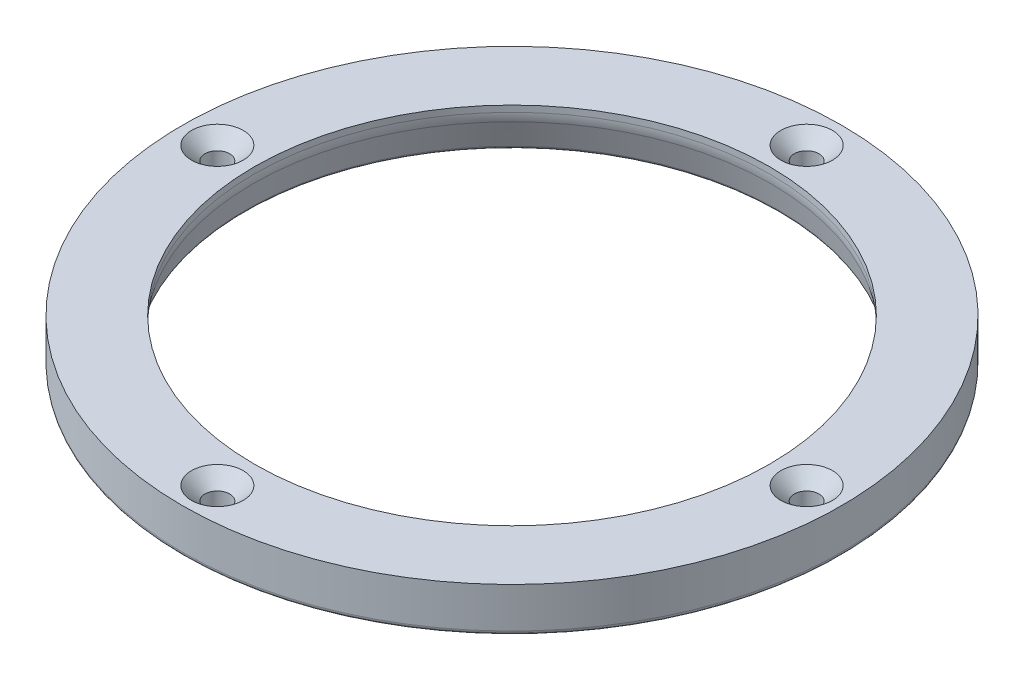
SolidWorks part; units mm, degrees
ref_plane "Front Plane" through (0, 0, 0) normal (0, 0, 1) x (1, 0, 0)
ref_plane "Top Plane" through (0, 0, 0) normal (0, 1, 0) x (1, 0, 0)
ref_plane "Right Plane" through (0, 0, 0) normal (1, 0, 0) x (0, 0, -1)
sketch "Sketch1" plane through (0, 0, 0) normal (0, 1, 0) x (1, 0, 0)
  circle A0 centre (0, 0) radius 59.944
  circle A1 centre (0, 0) radius 47.244
  dimension "D1" = 119.888
  dimension "D2" = 12.7
extrude "Boss-Extrude1" add sketch "Sketch1" along normal blind 8.128
sketch "Sketch2" plane through (0, 8.128, 0) normal (0, 1, 0) x (1, 0, 0)
  line L0 (0, 0) -> (0, 47.244) construction
  line L1 (0, 47.244) -> (0, 59.944) construction
  circle A0 centre (0, 0) radius 47.244 construction
  circle A1 centre (0, 0) radius 59.944 construction
  point P3 (0, 53.594)
  dimension "D1" = 53.594
hole_wizard "CSK for M4 Flat Head Machine Screw1" positions "3DSketch1" profile "Sketch3" countersink size "M4" standard "ANSI Metric" end condition through all
sketch3d "3DSketch1"
  point P0 (0, 8.128, -53.594)
sketch "Sketch3" plane through (0, 8.128, -53.594) normal (1, 0, 0) x (0, 0, 1)
  line L0 (0, 0) -> (0, 8.128)
  line L1 (0, 8.128) -> (2.25, 8.128)
  line L2 (2.25, 8.128) -> (2.25, 2.45)
  line L3 (2.25, 2.45) -> (4.7, 0)
  line L5 (4.7, 0) -> (0, 0)
  line L6 (-2.25, 2.45) -> (-4.7, 0) construction
  line L11 (0, -6.35) -> (0, 107.95) construction
  dimension "Thru Hole Dia." = 4.5
  dimension "Thru Hole Depth" = 8.128
  dimension "Near C'Sink Dia." = 9.4
  dimension "Near C'Sink Angle" = 90
pattern_circular "CirPattern1" count 4 over 360 about axis through (0, 0, 0) along (0, 1, 0) of "CSK for M4 Flat Head Machine Screw1"
draft "Draft1" [suppressed] type of draft neutral plane draft angle 5 faces to draft 1 parameters "D1"=5
draft "Draft2" type of draft neutral plane draft angle 15 faces to draft 1 face at (0, 8.128, 47.244) neutral plane through (0, 0, 0) neutral plane normal (0, -1, 0) parameters "D1"=15
sketch "Sketch4" plane through (0, 0, 0) normal (1, 0, 0) x (0, 0, -1)
  line L0 (47.244, 0) -> (45.0661, 8.128)
  line L1 (-47.244, 0) -> (47.244, 0) construction
  line L2 (-59.944, 0) -> (59.944, 0) construction
  line L3 (0, 8.128) -> (47.244, 8.128) construction
  line L4 (45.0661, 8.128) -> (46.3361, 8.128)
  line L5 (47.244, 8.128) -> (59.944, 8.128) construction
  line L6 (46.3361, 8.128) -> (48.514, 0)
  line L7 (48.514, 0) -> (47.244, 0)
  line L8 (45.0661, 8.128) -> (45.0661, 2.2364) construction
  dimension "D1" = 1.27
  dimension "D2" = 47.244
  dimension "D3" = 15
ref_axis "Axis1" through (0, 8.128, 0) along (0, -1, 0)
revolve "Cut-Revolve1" cut sketch "Sketch4" angle 360 about axis through (0, 8.128, 0) along (0, -1, 0)
sketch "Sketch5" plane through (0, 8.128, 0) normal (0, 1, 0) x (1, 0, 0)
  circle A2 centre (0, 0) radius 46.8653
  circle A3 centre (0, 0) radius 46.8653
  dimension "D1" = 0.5292
extrude "Cut-Extrude1" cut sketch "Sketch5" against normal through all
fillet "Fillet1" radius 6.35 1 edges at (0, 6.1531, -46.8653)
fillet "Fillet2" radius 0.7937 2 edges at (0, 0, 59.944) (0, 0, 48.514)
